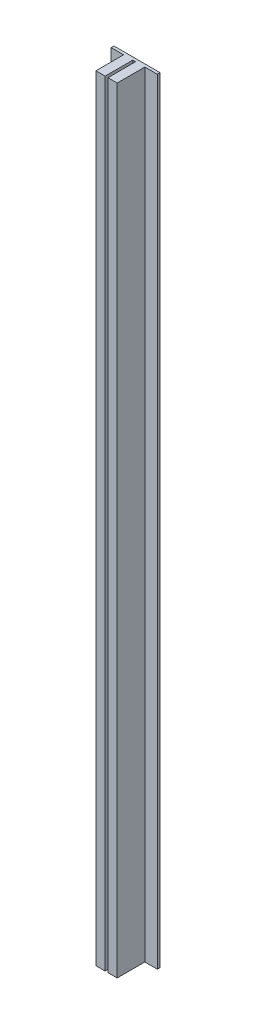
SolidWorks part; units mm, degrees
ref_plane "Front Plane" through (0, 0, 0) normal (0, 0, 1) x (1, 0, 0)
ref_plane "Top Plane" through (0, 0, 0) normal (0, 1, 0) x (1, 0, 0)
ref_plane "Right Plane" through (0, 0, 0) normal (1, 0, 0) x (0, 0, -1)
sketch "Sketch1" plane through (0, 0, 0) normal (0, 0, 1) x (1, 0, 0)
  line L1 (0, 0) -> (50, 0)
  line L2 (0, 0) -> (0, -840)
  line L3 (0, -840) -> (50, -840)
  line L4 (50, 0) -> (50, -840)
  dimension "D1" = 50
  dimension "D2" = 840
extrude "Boss-Extrude1" add sketch "Sketch1" along normal blind 3
sketch "Sketch2" plane through (0, 0, 3) normal (0, 0, 1) x (1, 0, 0)
  line L0 (25, 0) -> (25, -840) construction
  line L1 (50, 0) -> (0, 0) construction
  line L2 (0, -840) -> (50, -840) construction
  line L4 (13.5, 0) -> (36.5, 0)
  line L5 (13.5, 0) -> (13.5, -840)
  line L6 (13.5, -840) -> (36.5, -840)
  line L7 (36.5, 0) -> (36.5, -840)
  point P10 (25, -840)
  dimension "D1" = 23
extrude "Boss-Extrude2" add sketch "Sketch2" along normal blind 30
sketch "Sketch3" plane through (0, 0, 33) normal (0, 0, 1) x (1, 0, 0)
  line L0 (25, 0) -> (25, -840) construction
  line L1 (36.5, 0) -> (13.5, 0) construction
  line L2 (13.5, -840) -> (36.5, -840) construction
  line L4 (23.5, 0) -> (26.5, 0)
  line L5 (23.5, 0) -> (23.5, -840)
  line L6 (23.5, -840) -> (26.5, -840)
  line L7 (26.5, 0) -> (26.5, -840)
  point P10 (25, -840)
  dimension "D1" = 3
extrude "Cut-Extrude1" cut sketch "Sketch3" against normal up to surface (30 mm away) up to face at (6.75, -420, 3)
